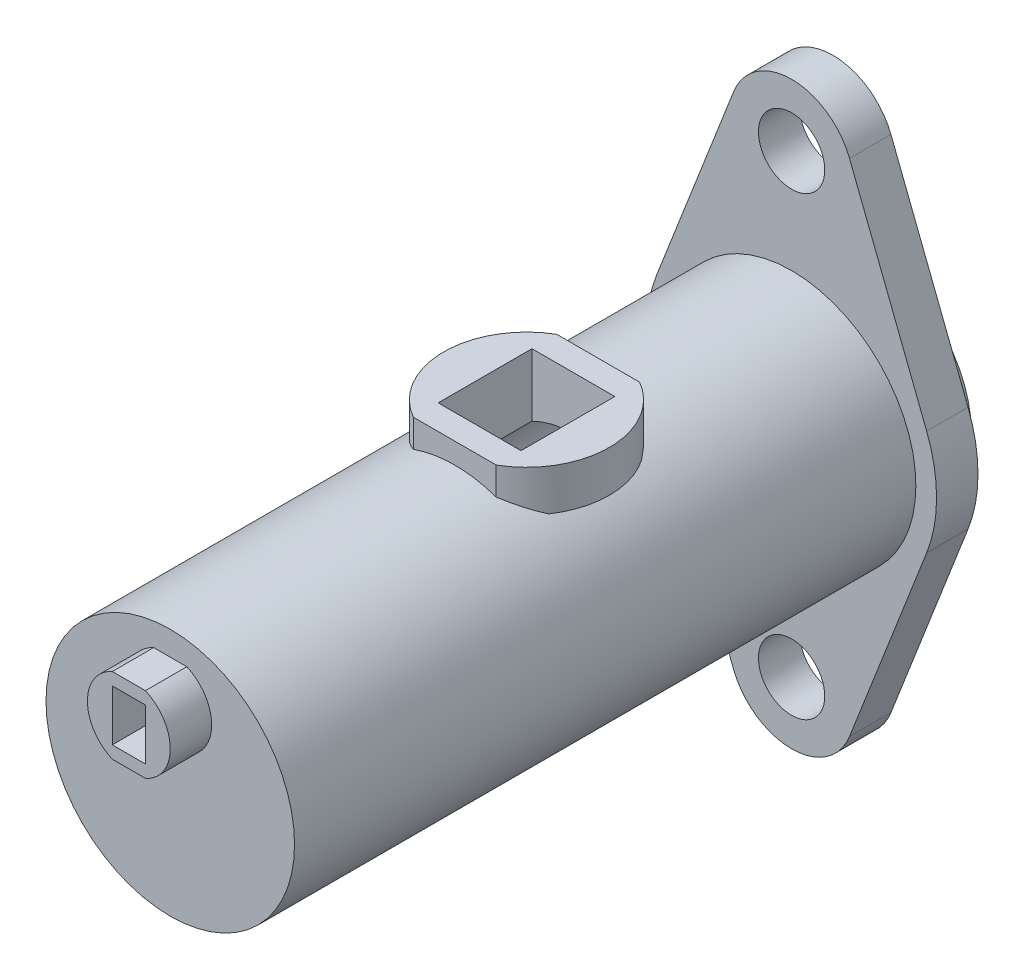
SolidWorks part; units mm, degrees
material "AISI 1020 Steel, Cold Rolled"
ref_plane "Front Plane" through (0, 0, 0) normal (0, 0, 1) x (1, 0, 0)
ref_plane "Top Plane" through (0, 0, 0) normal (0, 1, 0) x (1, 0, 0)
ref_plane "Right Plane" through (0, 0, 0) normal (1, 0, 0) x (0, 0, -1)
sketch "Sketch1" plane through (0, 0, 0) normal (0, 0, 1) x (1, 0, 0)
  line L0 (-46.9061, 0) -> (41.3847, 0) construction
  line L1 (-16.302, -6.3636) -> (-6.9866, -30.2273)
  line L2 (16.302, -6.3636) -> (6.9866, -30.2273)
  line L3 (16.302, 6.3636) -> (6.9866, 30.2273)
  line L4 (-16.302, 6.3636) -> (-6.9866, 30.2273)
  line L5 (0, 58.3872) -> (0, -64.9962) construction
  circle A0 centre (0, 0) radius 15
  arc A1 (16.302, -6.3636) -> (16.302, 6.3636) centre (0, 0) ccw
  circle A2 centre (0, 27.5) radius 4
  circle A3 centre (0, -27.5) radius 4
  arc A4 (-6.9866, -30.2273) -> (6.9866, -30.2273) centre (0, -27.5) ccw
  arc A5 (6.9866, 30.2273) -> (-6.9866, 30.2273) centre (0, 27.5) ccw
  arc A6 (-16.302, 6.3636) -> (-16.302, -6.3636) centre (0, 0) ccw
  point P20 (-17.5, 0)
  point P21 (17.5, 0)
  point P23 (0, 0)
  dimension "D1" = 30
  dimension "D2" = 35
  dimension "D4" = 8
  dimension "D5" = 8
  dimension "D6" = 15
  dimension "D3" = 55
extrude "Boss-Extrude1" add sketch "Sketch1" along normal blind 5
sketch "Sketch3" plane through (0, 0, 0) normal (0, 0, 1) x (1, 0, 0)
  circle A0 centre (0, 0) radius 15
  circle A1 centre (0, 0) radius 11.1125
  dimension "D1" = 30
  dimension "D2" = 22.225
extrude "Boss-Extrude2" add sketch "Sketch3" along normal blind 80
ref_plane "Plane1" through (0, 0, 80) normal (0, 0, 1) x (1, 0, 0)
sketch "Sketch4" plane through (0, 0, 80) normal (0, 0, 1) x (1, 0, 0)
  circle A0 centre (0, 0) radius 11.1125
extrude "Boss-Extrude3" add sketch "Sketch4" against normal blind 2
sketch "Sketch5" plane through (0, 0, 80) normal (0, 0, 1) x (1, 0, 0)
  line L0 (-2, 10.5826) -> (-2, 4.4174)
  line L1 (-2, 12.0826) -> (2, 12.0826)
  line L3 (-2, 2.9174) -> (2, 2.9174)
  line L5 (-2, 4.4174) -> (2, 4.4174)
  line L6 (2, 4.4174) -> (2, 10.5826)
  line L7 (2, 10.5826) -> (-2, 10.5826)
  arc A0 (-2, 12.0826) -> (-2, 2.9174) centre (0, 7.5) ccw
  arc A1 (2, 2.9174) -> (2, 12.0826) centre (0, 7.5) ccw
  point P2 (0, 12.0826)
  dimension "D1" = 7.5
  dimension "D2" = 10
  dimension "D3" = 4
  dimension "D4" = 1.5
  dimension "D5" = 1.5
extrude "Boss-Extrude4" add sketch "Sketch5" along normal blind 5
ref_plane "Plane2" through (0, 12.5, 0) normal (0, 1, 0) x (1, 0, 0)
sketch "Sketch6" plane through (0, 12.5, 0) normal (0, 1, 0) x (1, 0, 0)
  line L0 (2, -85) -> (-2, -85) construction
  line L1 (-5, -28.3397) -> (5, -28.3397)
  line L3 (-5, -45.6603) -> (5, -45.6603)
  line L5 (-5, -31.3397) -> (-5, -42.6603)
  line L6 (-5, -42.6603) -> (5, -42.6603)
  line L7 (5, -42.6603) -> (5, -31.3397)
  line L8 (5, -31.3397) -> (-5, -31.3397)
  arc A0 (-5, -28.3397) -> (-5, -45.6603) centre (0, -37) ccw
  arc A1 (5, -45.6603) -> (5, -28.3397) centre (0, -37) ccw
  point P9 (0, -45.6603)
  point P10 (0, -28.3397)
  dimension "D1" = 20
  dimension "D2" = 48
  dimension "D3" = 10
  dimension "D4" = 3
  dimension "D5" = 3
extrude "Boss-Extrude5" add sketch "Sketch6" along normal blind 5
sketch "Sketch7" plane through (0, 0, 0) normal (1, 0, 0) x (0, 0, -1)
  line L1 (0, 6.3636) -> (0, 30.2273) construction
  line L2 (0, 15) -> (4, 12.6906)
  line L3 (4, 12.6906) -> (4, 0)
  line L4 (4, 0) -> (0, 0)
  line L5 (0, 0) -> (0, 15)
  line L6 (-80, 15) -> (26.9475, 15) construction
  line L7 (-45.6603, 15) -> (-80, 15) construction
  dimension "D1" = 60
  dimension "D2" = 4
revolve "Revolve1" add sketch "Sketch7" angle 360 about L4
ref_plane "Plane3" through (0, 0, -4) normal (0, 0, -1) x (-1, 0, 0)
sketch "Sketch8" plane through (0, 0, -4) normal (0, 0, -1) x (-1, 0, 0)
  circle A0 centre (0, 0) radius 4
  dimension "D1" = 8
extrude "Cut-Extrude1" cut sketch "Sketch8" against normal blind 4
sketch "Sketch10" plane through (0, 0, 80) normal (0, 0, 1) x (1, 0, 0)
  line L4 (2, 4.4174) -> (2, 10.5826)
  line L5 (2, 10.5826) -> (-2, 10.5826)
  line L6 (-2, 10.5826) -> (-2, 4.4174)
  line L7 (-2, 4.4174) -> (2, 4.4174)
  line L8 (2, 4.4174) -> (2, 10.5826)
  line L9 (2, 10.5826) -> (-2, 10.5826)
  line L10 (-2, 10.5826) -> (-2, 4.4174)
  line L11 (-2, 4.4174) -> (2, 4.4174)
  dimension "D1" = 0
extrude "Cut-Extrude2" cut sketch "Sketch10" against normal blind 2
sketch "Sketch11" plane through (0, 12.5, 0) normal (0, 1, 0) x (1, 0, 0)
  line L0 (5, -42.6603) -> (-5, -42.6603) construction
  line L1 (5, -42.6603) -> (5, -31.3397) construction
  line L2 (-5, -31.3397) -> (5, -31.3397) construction
  line L3 (-5, -31.3397) -> (-5, -42.6603) construction
  line L4 (5, -42.6603) -> (-5, -42.6603)
  line L5 (5, -42.6603) -> (5, -31.3397)
  line L6 (-5, -31.3397) -> (5, -31.3397)
  line L7 (-5, -31.3397) -> (-5, -42.6603)
extrude "Cut-Extrude3" cut sketch "Sketch11" along normal mid plane 37
